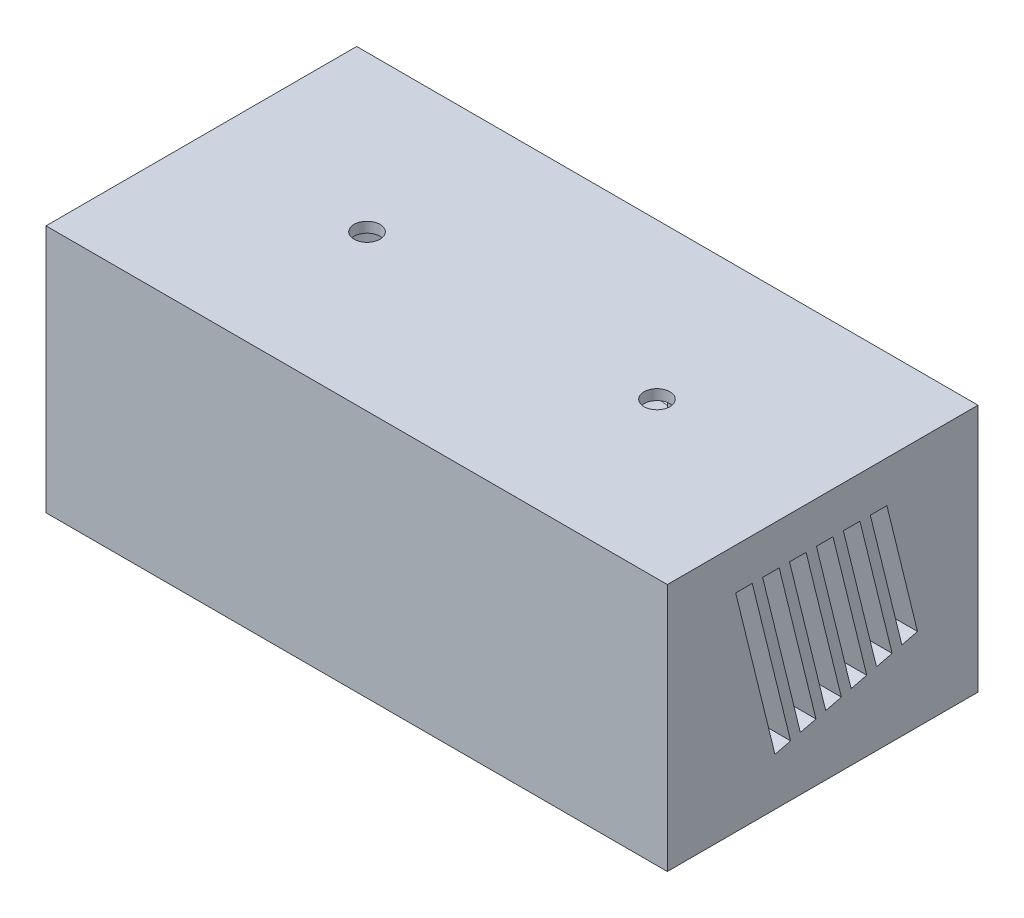
SolidWorks part; units mm, degrees
ref_plane "Front Plane" through (0, 0, 0) normal (0, 0, 1) x (1, 0, 0)
ref_plane "Top Plane" through (0, 0, 0) normal (0, 1, 0) x (1, 0, 0)
ref_plane "Right Plane" through (0, 0, 0) normal (1, 0, 0) x (0, 0, -1)
sketch "Sketch2" plane through (0, 0, 0) normal (0, 1, 0) x (1, 0, 0)
  line L0 (0, 75) -> (0, -75) construction
  line L1 (-150, 75) -> (150, 75)
  line L2 (-150, 75) -> (-150, -75)
  line L3 (-150, -75) -> (150, -75)
  line L4 (150, 75) -> (150, -75)
  line L5 (-150, 75) -> (150, -75) construction
  line L6 (-150, -75) -> (150, 75) construction
  line L7 (-100, 75) -> (-100, -75) construction
  line L8 (100, 75) -> (100, -75) construction
  line L10 (-135, 75) -> (-65, 75) construction
  line L11 (-135, 75) -> (-135, -75) construction
  line L12 (-135, -75) -> (-65, -75) construction
  line L13 (-65, 75) -> (-65, -75) construction
  line L14 (-135, 75) -> (-65, -75) construction
  line L15 (-135, -75) -> (-65, 75) construction
  point P0 (0, 0)
  point P12 (-100, 0)
  dimension "D1" = 150
  dimension "D2" = 300
  dimension "D3" = 100
  dimension "D4" = 100
  dimension "D5" = 70
  dimension "D6" = 150
extrude "Boss-Extrude1" add sketch "Sketch2" along normal blind 120
sketch "Sketch7" plane through (0, 0, 0) normal (0, -1, 0) x (1, 0, 0)
  line L0 (-150, -75) -> (-150, 75) construction
  line L1 (-120, 65) -> (120, 65)
  line L2 (-140, 45) -> (-140, -45)
  line L3 (-120, -65) -> (120, -65)
  line L4 (140, 45) -> (140, -45)
  line L7 (-150, 75) -> (150, 75) construction
  line L8 (150, -75) -> (-150, -75) construction
  line L9 (150, 75) -> (150, -75) construction
  arc A0 (-140, 45) -> (-120, 65) centre (-120, 45) cw
  arc A1 (-140, -45) -> (-120, -65) centre (-120, -45) ccw
  arc A2 (140, -45) -> (120, -65) centre (120, -45) cw
  arc A3 (120, 65) -> (140, 45) centre (120, 45) cw
  point P0 (0, 0)
  dimension "D1" = 10
  dimension "D2" = 10
  dimension "D3" = 20
  dimension "D4" = 20
  dimension "D5" = 20
  dimension "D6" = 10
  dimension "D7" = 10
extrude "Cut-Extrude2" cut sketch "Sketch7" against normal blind 5
sketch "Sketch8" plane through (0, 5, 0) normal (0, -1, 0) x (1, 0, 0)
  line L0 (-91.7157, 60) -> (91.7157, 60)
  line L1 (-135, 16.7157) -> (-135, -16.7157)
  line L2 (-91.7157, -60) -> (91.7157, -60)
  line L3 (135, 16.7157) -> (135, -16.7157)
  line L4 (-140, 45) -> (-140, -45) construction
  line L5 (-120, 65) -> (120, 65) construction
  line L6 (140, 45) -> (140, -45) construction
  line L7 (-120, -65) -> (120, -65) construction
  arc A0 (-135, 16.7157) -> (-91.7157, 60) centre (-91.7157, 16.7157) cw
  arc A1 (-135, -16.7157) -> (-91.7157, -60) centre (-91.7157, -16.7157) ccw
  arc A2 (91.7157, -60) -> (135, -16.7157) centre (91.7157, -16.7157) ccw
  arc A3 (91.7157, 60) -> (135, 16.7157) centre (91.7157, 16.7157) cw
  arc A4 (120, -65) -> (140, -45) centre (120, -45) ccw construction
  dimension "D5" = 40
  dimension "D1" = 5
  dimension "D2" = 5
  dimension "D3" = 5
  dimension "D4" = 5
extrude "Cut-Extrude3" cut sketch "Sketch8" against normal offset from surface (110 mm away) 5 up to face at (0, 120, 0)
sketch "Sketch15" plane through (150, 0, 0) normal (1, 0, 0) x (0, 0, -1)
  line L0 (-75, 120) -> (-75, 0) construction
  line L7 (-42, 100) -> (-23.0297, 23.0202)
  line L9 (-55, 100) -> (55, 100) construction
  line L10 (-75, 120) -> (75, 120) construction
  line L11 (75, 120) -> (75, 0) construction
  line L12 (-55, 100) -> (-35.2854, 20) construction
  line L29 (-35.2854, 20) -> (55, 42.2492) construction
  line L30 (55, 42.2492) -> (40.7684, 100) construction
  line L31 (-45, 0) -> (45, 0) construction
  line L32 (-47, 100) -> (-27.7435, 21.8586) construction
  line L33 (-55, 100) -> (-47, 100) construction
  line L34 (-23.0297, 23.0202) -> (-15.4877, 24.8788)
  line L35 (-15.4877, 24.8788) -> (-34, 100)
  line L36 (-34, 100) -> (-42, 100)
  line L37 (-29, 100) -> (-10.774, 26.0404)
  line L38 (-10.774, 26.0404) -> (-3.232, 27.899)
  line L39 (-3.232, 27.899) -> (-21, 100)
  line L40 (-21, 100) -> (-29, 100)
  line L45 (-16, 100) -> (1.4817, 29.0606)
  line L46 (1.4817, 29.0606) -> (9.0237, 30.9192)
  line L47 (9.0237, 30.9192) -> (-8, 100)
  line L48 (-8, 100) -> (-16, 100)
  line L49 (-3, 100) -> (13.7375, 32.0808)
  line L50 (13.7375, 32.0808) -> (21.2794, 33.9394)
  line L51 (21.2794, 33.9394) -> (5, 100)
  line L52 (5, 100) -> (-3, 100)
  line L57 (10, 100) -> (25.9932, 35.101)
  line L58 (25.9932, 35.101) -> (33.5352, 36.9596)
  line L59 (33.5352, 36.9596) -> (18, 100)
  line L60 (18, 100) -> (10, 100)
  line L61 (23, 100) -> (38.2489, 38.1212)
  line L62 (38.2489, 38.1212) -> (45.7909, 39.9798)
  line L63 (45.7909, 39.9798) -> (31, 100)
  line L64 (31, 100) -> (23, 100)
  line L65 (36, 100) -> (44, 100) construction
  line L66 (44, 100) -> (58.0466, 43) construction
  line L67 (58.0466, 43) -> (50.5046, 41.1414) construction
  line L68 (50.5046, 41.1414) -> (36, 100) construction
  line L69 (-35.2854, 20) -> (-27.7435, 21.8586) construction
  point P16 (-75, 60)
  dimension "D1" = 20
  dimension "D2" = 20
  dimension "D3" = 20
  dimension "D4" = 90
  dimension "D5" = 20
  dimension "D6" = 8
  dimension "D7" = 77
  dimension "D8" = 8
  dimension "D9" = 8
  dimension "D10" = 5
  dimension "D11" = 8
  dimension "D12" = 8
  dimension "D13" = 5
  dimension "D14" = 5
  dimension "D15" = 5
  dimension "D16" = 5
  dimension "D17" = 5
  dimension "D18" = 8
  dimension "D19" = 5
  dimension "D20" = 8
  dimension "D21" = 8
hole_wizard "CBORE for M4 Pan Head Machine Screw1" positions "Sketch13" profile "Sketch14" counterbore size "M4" standard "ANSI Metric"
sketch "Sketch13" plane through (0, 0, 0) normal (0, -1, 0) x (-1, 0, 0)
  line L1 (120, -65) -> (-120, -65) construction
  line L2 (140, -45) -> (140, 45) construction
  point P0 (-128, 53)
  point P2 (128, 53)
  point P4 (128, -53)
  point P6 (-128, -53)
  dimension "D1" = 12
  dimension "D2" = 12
  dimension "D3" = 12
  dimension "D4" = 12
sketch "Sketch14" plane through (128, 0, -53) normal (1, 0, 0) x (0, 0, -1)
  line L0 (0, 0) -> (0, 31.3519)
  line L1 (0, 31.3519) -> (2.25, 30)
  line L2 (2.25, 30) -> (2.25, 3.1)
  line L3 (2.25, 3.1) -> (4.5, 3.1)
  line L5 (4.5, 3.1) -> (4.5, 0.025)
  line L6 (4.5, 0.025) -> (4.525, 0)
  line L7 (4.525, 0) -> (0, 0)
  line L8 (-4.5, 0.025) -> (-4.525, 0) construction
  line L10 (0, 31.3519) -> (-2.25, 30) construction
  line L11 (0, -6.35) -> (0, 107.95) construction
  dimension "Hole Dia." = 4.5
  dimension "Hole Depth" = 30
  dimension "C'Bore Dia." = 9
  dimension "C'Bore Depth" = 3.1
  dimension "Near C'Sink Dia." = 9.05
  dimension "Near C'Sink Angle" = 90
  dimension "Drill Angle" = 118
extrude "Cut-Extrude5" cut sketch "Sketch15" against normal through all
sketch "Sketch17" plane through (0, 0, -75) normal (0, 0, -1) x (-1, 0, 0)
  line L0 (-150, 120) -> (-150, 0) construction
  circle A0 centre (0, 60) radius 15
  point P3 (-150, 60)
  dimension "D1" = 30
extrude "Cut-Extrude6" cut sketch "Sketch17" against normal blind 20
sketch "Sketch3" plane through (0, 120, 0) normal (0, 1, 0) x (1, 0, 0)
  line L0 (0, 75) -> (0, -75) construction
  circle A1 centre (-70, 0) radius 6.25
  circle A2 centre (70, 0) radius 6.25
  dimension "D1" = 12.5
  dimension "50" = 70
extrude "Cut-Extrude1" cut sketch "Sketch3" against normal blind 50
